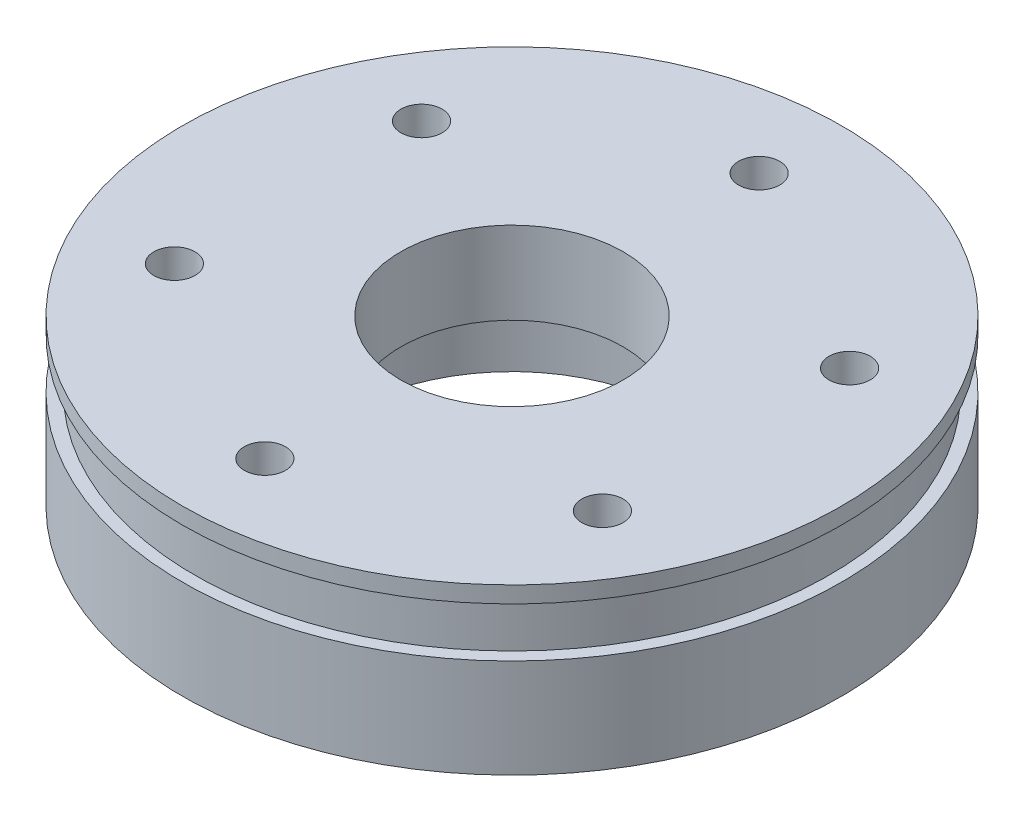
SolidWorks part; units mm, degrees
ref_plane "Front Plane" through (0, 0, 0) normal (0, 0, 1) x (1, 0, 0)
ref_plane "Top Plane" through (0, 0, 0) normal (0, 1, 0) x (1, 0, 0)
ref_plane "Right Plane" through (0, 0, 0) normal (1, 0, 0) x (0, 0, -1)
sketch "Sketch1" plane through (0, 0, 0) normal (0, 1, 0) x (1, 0, 0)
  circle A0 centre (0, 0) radius 38.515
  dimension "D1" = 77.03
extrude "Boss-Extrude1" add sketch "Sketch1" along normal blind 10
sketch "Sketch2" plane through (0, 10, 0) normal (0, 1, 0) x (1, 0, 0)
  circle A0 centre (0, 0) radius 40
  dimension "D1" = 80
extrude "Boss-Extrude2" add sketch "Sketch2" against normal blind 2
sketch "Sketch3" plane through (0, 0, 0) normal (0, -1, 0) x (1, 0, 0)
  circle A0 centre (0, 0) radius 40
  dimension "D1" = 80
extrude "Boss-Extrude3" add sketch "Sketch3" against normal blind 2 and the other way blind 10
sketch "Sketch4" plane through (0, -10, 0) normal (0, -1, 0) x (1, 0, 0)
  circle A0 centre (0, 0) radius 13.5
  circle A1 centre (0, 0) radius 30 construction
  circle A2 centre (0, 30) radius 2.5
  circle A3 centre (25.9808, 15) radius 2.5
  circle A4 centre (25.9808, -15) radius 2.5
  circle A5 centre (0, -30) radius 2.5
  circle A6 centre (-25.9808, -15) radius 2.5
  circle A7 centre (-25.9808, 15) radius 2.5
  point P18 (0, 0)
  dimension "D1" = 5
  dimension "D2" = 27
  dimension "D3" = 60
  dimension "D4" = 6
extrude "Cut-Extrude1" cut sketch "Sketch4" against normal through all
sketch "Sketch5" plane through (0, -10, 0) normal (0, -1, 0) x (1, 0, 0)
  circle A0 centre (0, 0) radius 20
  dimension "D1" = 40
extrude "Cut-Extrude2" cut sketch "Sketch5" against normal blind 10
